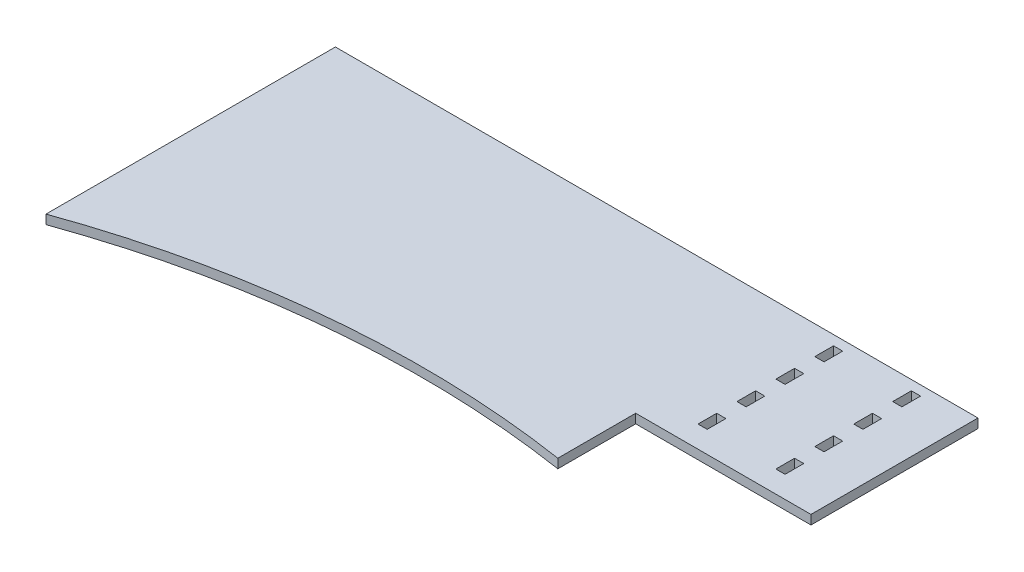
SolidWorks part; units mm, degrees
ref_plane "Front Plane" through (0, 0, 0) normal (0, 0, 1) x (1, 0, 0)
ref_plane "Top Plane" through (0, 0, 0) normal (0, 1, 0) x (1, 0, 0)
ref_plane "Right Plane" through (0, 0, 0) normal (1, 0, 0) x (0, 0, -1)
sketch "Sketch1" plane through (0, 0, 0) normal (0, 1, 0) x (1, 0, 0)
  line L1 (104.775, -50.8) -> (-104.775, -50.8)
  line L2 (104.775, -50.8) -> (104.775, 50.8)
  line L3 (104.775, 50.8) -> (-104.775, 50.8)
  line L4 (-104.775, -50.8) -> (-104.775, 50.8)
  line L5 (104.775, -50.8) -> (-104.775, 50.8) construction
  line L6 (104.775, 50.8) -> (-104.775, -50.8) construction
  point P0 (0, 0)
  dimension "D1" = 209.55
  dimension "D2" = 101.6
extrude "Boss-Extrude1" add sketch "Sketch1" along normal mid plane 3
sketch "Sketch2" plane through (0, 1.5, 0) normal (0, 1, 0) x (1, 0, 0)
  line L0 (-83.8536, -25.4) -> (77.2071, -25.4) construction
  line L1 (-104.775, -50.8) -> (104.775, -50.8) construction
  circle A0 centre (0, -336.55) radius 311.15
  dimension "D1" = 622.3
  dimension "D2" = 25.4
extrude "Cut-Extrude1" cut sketch "Sketch2" against normal through all both and the other way through all
sketch "Sketch3" plane through (0, -1.5, 0) normal (0, -1, 0) x (1, 0, 0)
  line L0 (-104.775, -50.8) -> (-104.775, 43.5713) construction
  line L1 (-101.6, 27.0153) -> (-101.6, 7.9653) construction
  line L2 (-101.6, 7.9653) -> (-101.6, -11.0847) construction
  circle A0 centre (-101.6, 7.9653) radius 1.5875
  circle A1 centre (-101.6, 27.0153) radius 1.5875
  circle A2 centre (-101.6, -11.0847) radius 1.5875
  dimension "D1" = 3.175
  dimension "D2" = 3.175
  dimension "D3" = 19.05
sketch "Sketch4" plane through (0, 1.5, 0) normal (0, 1, 0) x (1, 0, 0)
  line L0 (47.625, -29.0664) -> (47.625, -3.6664)
  line L1 (47.625, -3.6664) -> (104.775, -3.6664)
  line L2 (104.775, -43.5713) -> (104.775, 50.8) construction
  line L3 (104.775, -3.6664) -> (104.775, -43.5713)
  line L4 (104.775, -43.5713) -> (47.625, -29.0664)
  arc A0 (104.775, -43.5713) -> (-104.775, -43.5713) centre (0, -336.55) ccw construction
  dimension "D1" = 57.15
  dimension "D2" = 25.4
extrude "Cut-Extrude2" cut sketch "Sketch4" against normal through all both and the other way through all
sketch "Sketch5" plane through (0, 1.5, 0) normal (0, 1, 0) x (1, 0, 0)
  line L0 (104.775, 50.8) -> (-104.775, 50.8) construction
  line L1 (86.233, 47.625) -> (89.233, 47.625)
  line L2 (86.233, 47.625) -> (86.233, 41.529)
  line L3 (86.233, 41.529) -> (89.233, 41.529)
  line L4 (89.233, 47.625) -> (89.233, 41.529)
  line L5 (104.775, -3.6664) -> (104.775, 50.8) construction
  line L6 (86.233, 34.925) -> (86.233, 28.829)
  line L7 (89.233, 34.925) -> (89.233, 28.829)
  line L8 (86.233, 34.925) -> (89.233, 34.925)
  line L9 (86.233, 28.829) -> (89.233, 28.829)
  line L10 (86.233, 22.225) -> (86.233, 16.129)
  line L11 (89.233, 22.225) -> (89.233, 16.129)
  line L12 (86.233, 22.225) -> (89.233, 22.225)
  line L13 (86.233, 16.129) -> (89.233, 16.129)
  line L14 (86.233, 9.525) -> (86.233, 3.429)
  line L15 (89.233, 9.525) -> (89.233, 3.429)
  line L16 (86.233, 9.525) -> (89.233, 9.525)
  line L17 (86.233, 3.429) -> (89.233, 3.429)
  line L18 (60.833, 34.925) -> (60.833, 28.829)
  line L19 (63.833, 34.925) -> (63.833, 28.829)
  line L20 (60.833, 34.925) -> (63.833, 34.925)
  line L21 (60.833, 28.829) -> (63.833, 28.829)
  line L22 (60.833, 22.225) -> (60.833, 16.129)
  line L23 (63.833, 22.225) -> (63.833, 16.129)
  line L24 (60.833, 22.225) -> (63.833, 22.225)
  line L25 (60.833, 16.129) -> (63.833, 16.129)
  line L26 (60.833, 9.525) -> (60.833, 3.429)
  line L27 (63.833, 9.525) -> (63.833, 3.429)
  line L28 (60.833, 9.525) -> (63.833, 9.525)
  line L29 (60.833, 3.429) -> (63.833, 3.429)
  line L30 (60.833, 47.625) -> (60.833, 41.529)
  line L31 (63.833, 47.625) -> (63.833, 41.529)
  line L32 (60.833, 47.625) -> (63.833, 47.625)
  line L33 (60.833, 41.529) -> (63.833, 41.529)
  line L34 (86.233, 47.625) -> (86.233, 34.925) construction
  line L35 (86.233, 47.625) -> (60.833, 47.625) construction
  dimension "D1" = 3
  dimension "D2" = 6.096
  dimension "D3" = 3.175
  dimension "D4" = 18.542
  dimension "D5" = 12.7
  dimension "D6" = 25.4
extrude "Cut-Extrude3" cut sketch "Sketch5" against normal through all both and the other way through all
